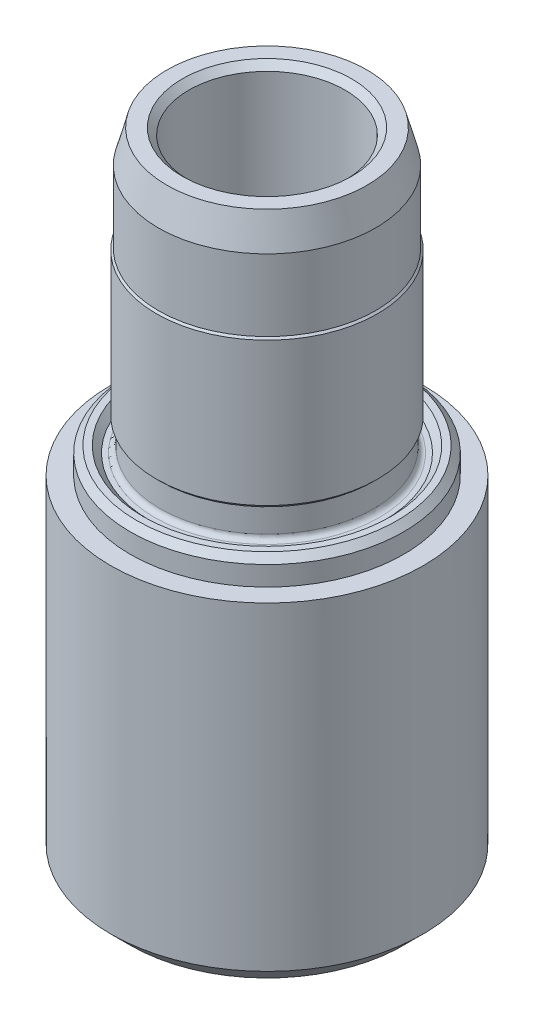
SolidWorks part; units mm, degrees
ref_plane "Plan1" through (0, 0, 0) normal (0, 0, 1) x (1, 0, 0)
ref_plane "Plan2" through (0, 0, 0) normal (0, 1, 0) x (1, 0, 0)
ref_plane "Plan3" through (0, 0, 0) normal (1, 0, 0) x (0, 0, -1)
sketch "Esquisse1" plane through (0, 0, 0) normal (0, 0, 1) x (1, 0, 0)
  line L0 (0, 0) -> (7.6801, 0)
  line L1 (7.6801, 0) -> (8.35, -2.5)
  line L2 (8.35, -2.5) -> (8.35, -8)
  line L3 (8.35, -8) -> (8.49, -8.14)
  line L4 (8.49, -8.14) -> (8.49, -19.14)
  line L5 (8.49, -19.14) -> (8.21, -19.42)
  line L6 (8.21, -19.42) -> (8.21, -21.24)
  line L7 (8.61, -21.64) -> (8.99, -21.64)
  line L8 (8.99, -21.64) -> (9.49, -21.14)
  line L9 (9.49, -21.14) -> (10, -21.14)
  line L10 (10, -21.14) -> (12, -23.14)
  line L11 (12, -23.14) -> (12, -40.64)
  line L12 (12, -40.64) -> (10, -42.64)
  line L13 (11, -44.14) -> (19, -44.14)
  line L14 (19, -44.14) -> (19, -45.14)
  line L15 (19, -45.14) -> (12.0718, -49.14)
  line L16 (12.0718, -49.14) -> (0, -49.14)
  line L17 (0, -10) -> (0, -40) construction
  line L18 (10, -42.64) -> (10, -43.14)
  line L19 (0, 0) -> (0, -49.14)
  arc A0 (11, -44.14) -> (10, -43.14) centre (11, -43.14) cw
  arc A1 (8.61, -21.64) -> (8.21, -21.24) centre (8.61, -21.24) cw
  dimension "D20" = 1
  dimension "D21" = 0.4
  dimension "D1" = 8.35
  dimension "D2" = 8.49
  dimension "D3" = 12
  dimension "D4" = 19
  dimension "D5" = 15
  dimension "D6" = 45
  dimension "D7" = 60
  dimension "D8" = 8.21
  dimension "D9" = 11
  dimension "D10" = 5.5
  dimension "D11" = 2
  dimension "D12" = 23
  dimension "D13" = 5
  dimension "D14" = 1.5
  dimension "D15" = 0.5
  dimension "D16" = 1
  dimension "D17" = 2.5
  dimension "D18" = 2
  dimension "D19" = 1
revolve "Base-Révolution" add sketch "Esquisse1" angle 360 about L17
hole_wizard "Perçage tête" positions "Esquisse3" profile "Esquisse2" legacy
sketch "Esquisse3" plane through (0, -49.14, 0) normal (0, -1, 0) x (1, 0, 0)
  point P0 (0, 0)
sketch "Esquisse2" plane through (0, -49.14, 0) normal (1, 0, 0) x (0, 0, -1)
  line L0 (0, 0) -> (0, 23.6052)
  line L1 (0, 23.6052) -> (6, 20)
  line L2 (6, 20) -> (6, 1.5)
  line L3 (6, 1.5) -> (7.5, 0)
  line L4 (7.5, 0) -> (0, 0)
  line L5 (0, -14.3089) -> (0, 102.4216) construction
  line L6 (0, 23.6052) -> (-6, 20) construction
  line L7 (-6, 1.5) -> (-7.5, 0) construction
  dimension "Diamètre" = 12
  dimension "Profondeur" = 20
  dimension "Diamètre fraisé" = 15
  dimension "Angle fraisé" = 90
  dimension "Angle" = 118
sketch "Esquisse4" plane through (0, -49.14, 0) normal (0, -1, 0) x (1, 0, 0)
  line L0 (-0.25, 6.7839) -> (-5.75, 3.6084)
  line L1 (0.25, 6.7839) -> (5.75, 3.6084)
  line L2 (6, 3.1754) -> (6, -3.1754)
  line L3 (5.75, -3.6084) -> (0.25, -6.7839)
  line L4 (-0.25, -6.7839) -> (-5.75, -3.6084)
  line L5 (-6, -3.1754) -> (-6, 3.1754)
  circle A2 centre (0, 0) radius 6 construction
  arc A3 (0.25, 6.7839) -> (-0.25, 6.7839) centre (0, 6.3509) ccw
  arc A4 (6, 3.1754) -> (5.75, 3.6084) centre (5.5, 3.1754) ccw
  arc A5 (5.75, -3.6084) -> (6, -3.1754) centre (5.5, -3.1754) ccw
  arc A6 (-0.25, -6.7839) -> (0.25, -6.7839) centre (0, -6.3509) ccw
  arc A7 (-6, -3.1754) -> (-5.75, -3.6084) centre (-5.5, -3.1754) ccw
  arc A8 (-5.75, 3.6084) -> (-6, 3.1754) centre (-5.5, 3.1754) ccw
  point P10 (0, 6.9282)
  point P17 (0, -6.9282)
  dimension "D2" = 0.5
  dimension "D1" = 120
extrude "Héxagone" cut sketch "Esquisse4" against normal blind 12
hole_wizard "Centrage" positions "Esquisse6" profile "Esquisse5" legacy
sketch "Esquisse6" plane through (0, 0, 0) normal (0, 1, 0) x (-1, 0, 0)
  point P0 (0, 0)
sketch "Esquisse5" plane through (0, 0, 0) normal (1, 0, 0) x (0, 0, 1)
  line L0 (0, 0) -> (0, 6.9013)
  line L1 (0, 6.9013) -> (1.5, 6)
  line L2 (1.5, 6) -> (1.5, 1.7321)
  line L3 (1.5, 1.7321) -> (2.5, 0)
  line L4 (2.5, 0) -> (0, 0)
  line L5 (0, -14.3089) -> (0, 102.4216) construction
  line L6 (0, 6.9013) -> (-1.5, 6) construction
  line L7 (-1.5, 1.7321) -> (-2.5, 0) construction
  dimension "Diamètre" = 3
  dimension "Profondeur" = 6
  dimension "Diamètre fraisé" = 5
  dimension "Angle fraisé" = 60
  dimension "Angle" = 118
hole_wizard "Perçage axe" positions "Esquisse8" profile "Esquisse7" legacy
sketch "Esquisse8" plane through (0, 0, 0) normal (0, 1, 0) x (-1, 0, 0)
  point P0 (0, 0)
sketch "Esquisse7" plane through (0, 0, 0) normal (1, 0, 0) x (0, 0, 1)
  line L0 (0, 0) -> (0, 15.6052)
  line L1 (0, 15.6052) -> (6, 12)
  line L2 (6, 12) -> (6, 0.5)
  line L3 (6, 0.5) -> (6.5, 0)
  line L4 (6.5, 0) -> (0, 0)
  line L5 (0, -14.3089) -> (0, 102.4216) construction
  line L6 (0, 15.6052) -> (-6, 12) construction
  line L7 (-6, 0.5) -> (-6.5, 0) construction
  dimension "Diamètre" = 12
  dimension "Profondeur" = 12
  dimension "Diamètre fraisé" = 13
  dimension "Angle fraisé" = 90
  dimension "Angle" = 118
sketch "Esquisse9" plane through (0, 0, 0) normal (0, 0, 1) x (1, 0, 0)
  line L0 (12, -40.64) -> (12, -23.14) construction
  line L1 (12, -40.64) -> (19, -40.64)
  line L2 (12, -40.64) -> (12, -49.14)
  line L3 (12, -49.14) -> (19, -49.14)
  line L4 (19, -40.64) -> (19, -49.14)
  line L5 (12, -40.64) -> (-12, -40.64) construction
  line L6 (19, -45.14) -> (19, -44.14) construction
  line L7 (-12.0718, -49.14) -> (12.0718, -49.14) construction
  line L8 (0, -50) -> (0, -34.3741) construction
  line L9 (0, -49.14) -> (0, -48.4285) construction
  line L11 (12, -21.14) -> (10.5, -21.14)
  line L12 (12, -21.14) -> (12, -23.14)
  line L13 (12, -23.14) -> (10.5, -23.14)
  line L14 (10.5, -21.14) -> (10.5, -23.14)
  line L19 (10, -21.14) -> (-10, -21.14) construction
  line L20 (12, -23.14) -> (-12, -23.14) construction
  dimension "D1" = 1.5
revolve "Enlèvement tête" cut sketch "Esquisse9" angle 360 about L8
sketch "Esquisse10" plane through (0, 0, 0) normal (0, 0, 1) x (1, 0, 0)
  line L0 (12, -40.64) -> (-12, -40.64) construction
  line L1 (10, -40.64) -> (12, -40.64)
  line L2 (10, -40.64) -> (10, -49.14)
  line L3 (10, -49.14) -> (12, -49.14)
  line L4 (12, -49.14) -> (12, -40.64)
  line L6 (10, -43.14) -> (10, -42.64) construction
  line L8 (-12, -49.14) -> (12, -49.14) construction
  line L10 (0, -47.9969) -> (0, -35.4022) construction
  line L11 (0, -12) -> (0, -15.6052) construction
  line L12 (12, -40.64) -> (12, -23.14) construction
revolve "Suppression gorge" add sketch "Esquisse10" angle 360 about L10
chamfer "Chanfrein1" distance 1.5 angle 45 1 edges at (0, -49.14, -12)
equation "\"D8@Esquisse1\" = \"D2@Esquisse1\"-2*(\"D2@Esquisse1\"-\"D1@Esquisse1\")"
